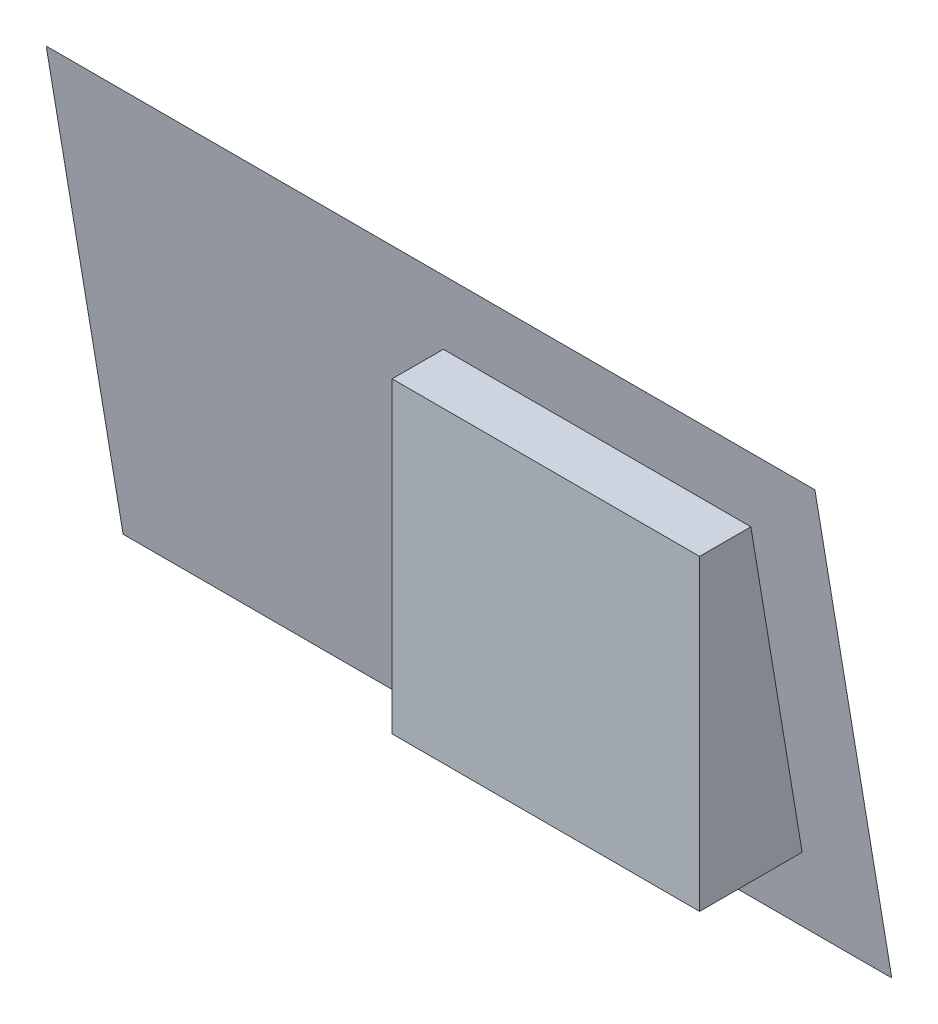
SolidWorks part; units mm, degrees
ref_plane "Front Plane" through (0, 0, 0) normal (0, 0, 1) x (1, 0, 0)
ref_plane "Top Plane" through (0, 0, 0) normal (0, 1, 0) x (1, 0, 0)
ref_plane "Right Plane" through (0, 0, 0) normal (1, 0, 0) x (0, 0, -1)
sketch "Sketch1" plane through (0, 0, 0) normal (0, 0, 1) x (1, 0, 0)
  line L1 (0, 0) -> (40, 0)
  line L2 (0, 0) -> (0, 40)
  line L3 (0, 40) -> (40, 40)
  line L4 (40, 0) -> (40, 40)
extrude "Boss-Extrude1" add sketch "Sketch1" along normal blind 20
sketch "Sketch2" plane through (0, 0, 0) normal (1, 0, 0) x (0, 0, -1)
  line L0 (-5, -10) -> (-15, 50)
surface "Surface-Extrude1" sketch "Sketch2" parameters "D1"=50, "D2"=50, "D3"=0, "D4"=0
other "SurfaceCut1"
